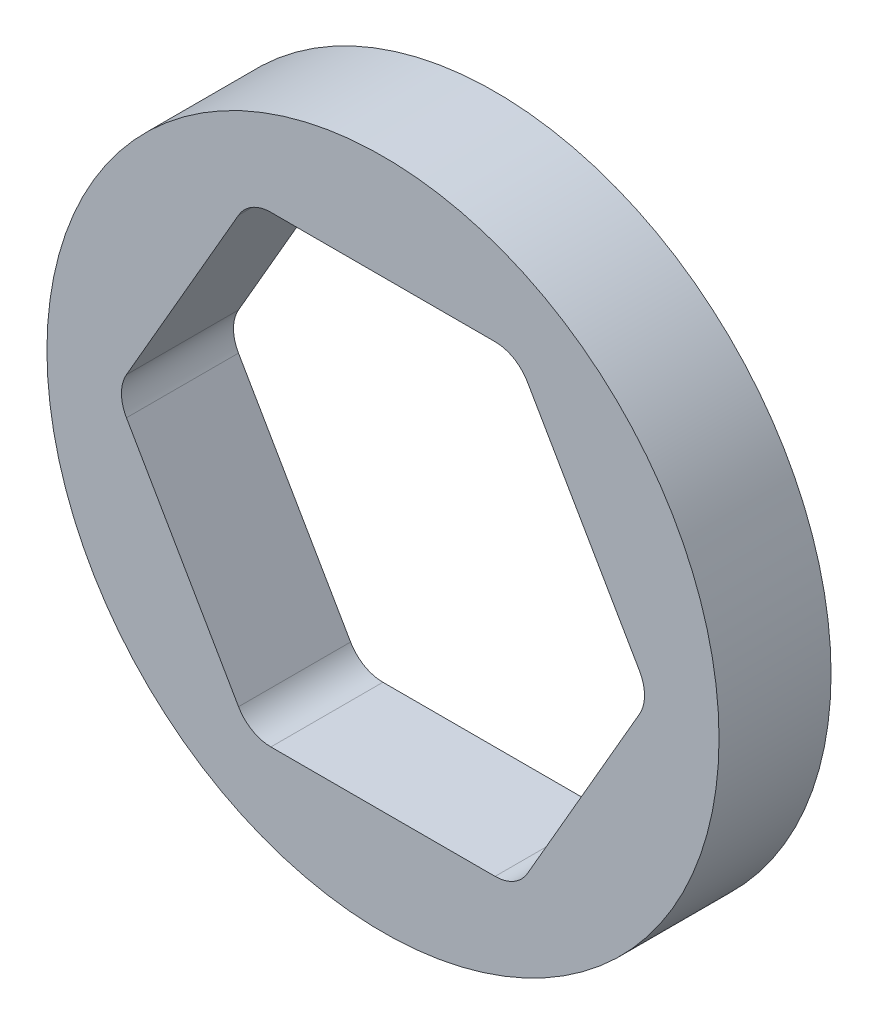
SolidWorks part; units mm, degrees
ref_plane "Front Plane" through (0, 0, 0) normal (0, 0, 1) x (1, 0, 0)
ref_plane "Top Plane" through (0, 0, 0) normal (0, 1, 0) x (1, 0, 0)
ref_plane "Right Plane" through (0, 0, 0) normal (1, 0, 0) x (0, 0, -1)
ref_plane "Plane1" through (0, 0, 3) normal (0, 0, 1) x (1, 0, 0)
sketch "Sketch1" plane through (0, 0, 3) normal (0, 0, 1) x (1, 0, 0)
  line L0 (-3.0022, 6.2) -> (3.0022, 6.2)
  line L1 (3.8682, 5.7) -> (6.8705, 0.5)
  line L2 (6.8705, -0.5) -> (3.8682, -5.7)
  line L3 (3.0022, -6.2) -> (-3.0022, -6.2)
  line L4 (-3.8682, -5.7) -> (-6.8705, -0.5)
  line L5 (-6.8705, 0.5) -> (-3.8682, 5.7)
  arc A0 (3.0022, 6.2) -> (3.8682, 5.7) centre (3.0022, 5.2) cw
  arc A1 (6.8705, 0.5) -> (6.8705, -0.5) centre (6.0044, 0) cw
  arc A2 (3.8682, -5.7) -> (3.0022, -6.2) centre (3.0022, -5.2) cw
  arc A3 (-3.0022, -6.2) -> (-3.8682, -5.7) centre (-3.0022, -5.2) cw
  arc A4 (-6.8705, -0.5) -> (-6.8705, 0.5) centre (-6.0044, 0) cw
  arc A5 (-3.8682, 5.7) -> (-3.0022, 6.2) centre (-3.0022, 5.2) cw
  circle A6 centre (0, 0) radius 9
extrude "Boss-Extrude1" add sketch "Sketch1" against normal blind 3
